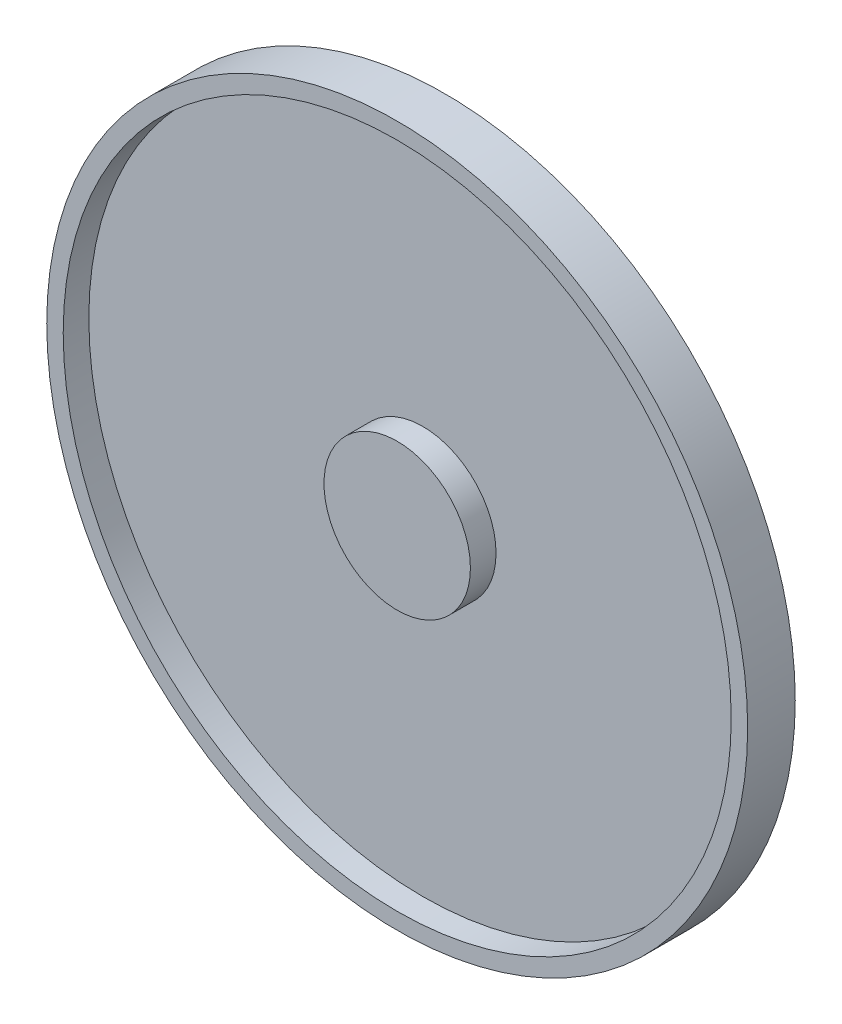
SolidWorks part; units mm, degrees
ref_plane "Front Plane" through (0, 0, 0) normal (0, 0, 1) x (1, 0, 0)
ref_plane "Top Plane" through (0, 0, 0) normal (0, 1, 0) x (1, 0, 0)
ref_plane "Right Plane" through (0, 0, 0) normal (1, 0, 0) x (0, 0, -1)
sketch "Sketch1" plane through (0, 0, 0) normal (0, 0, 1) x (1, 0, 0)
  line L0 (0, 0) -> (0, 397321.3981) construction
  line L1 (0, 0) -> (397321.3981, 0) construction
  circle A0 centre (0, 0) radius 478.75
  dimension "D1" = 957.5
extrude "Boss-Extrude1" add sketch "Sketch1" against normal blind 65
sketch "Sketch2" plane through (0, 0, 0) normal (0, 0, 1) x (1, 0, 0)
  circle A0 centre (0, 0) radius 100
  circle A1 centre (0, 0) radius 456.25
  dimension "D1" = 200
  dimension "D2" = 912.5
extrude "Cut-Extrude1" cut sketch "Sketch2" against normal offset from surface (35 mm away) 30 up to face at (478.75, 0, -65)
equation "\"A\"= 65.00"
equation "\"B\"= 957.50"
equation "\"D1@Sketch1\"=\"B\""
equation "\"D1@Boss-Extrude1\"=\"A\""
